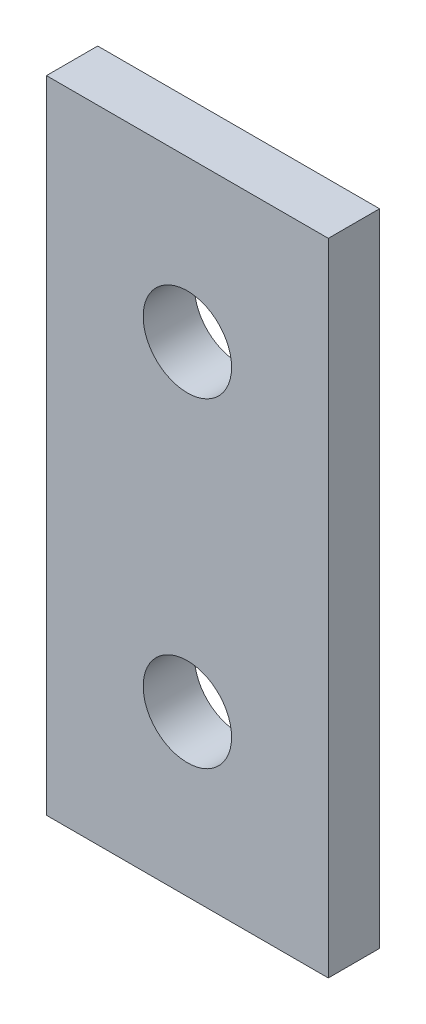
SolidWorks part; units mm, degrees
ref_plane "Front Plane" through (0, 0, 0) normal (0, 0, 1) x (1, 0, 0)
ref_plane "Top Plane" through (0, 0, 0) normal (0, 1, 0) x (1, 0, 0)
ref_plane "Right Plane" through (0, 0, 0) normal (1, 0, 0) x (0, 0, -1)
sketch "Sketch1" plane through (0, 0, 0) normal (0, 0, 1) x (1, 0, 0)
  line L1 (-24.7333, 2.2662) -> (-2.7333, 2.2662)
  line L2 (-24.7333, 2.2662) -> (-24.7333, -47.7338)
  line L3 (-24.7333, -47.7338) -> (-2.7333, -47.7338)
  line L4 (-2.7333, 2.2662) -> (-2.7333, -47.7338)
  circle A0 centre (-13.7333, -10.2338) radius 3.45
  circle A1 centre (-13.7333, -35.2338) radius 3.45
  dimension "D1" = 50
  dimension "D2" = 22
extrude "Extrude1" add sketch "Sketch1" along normal blind 4
